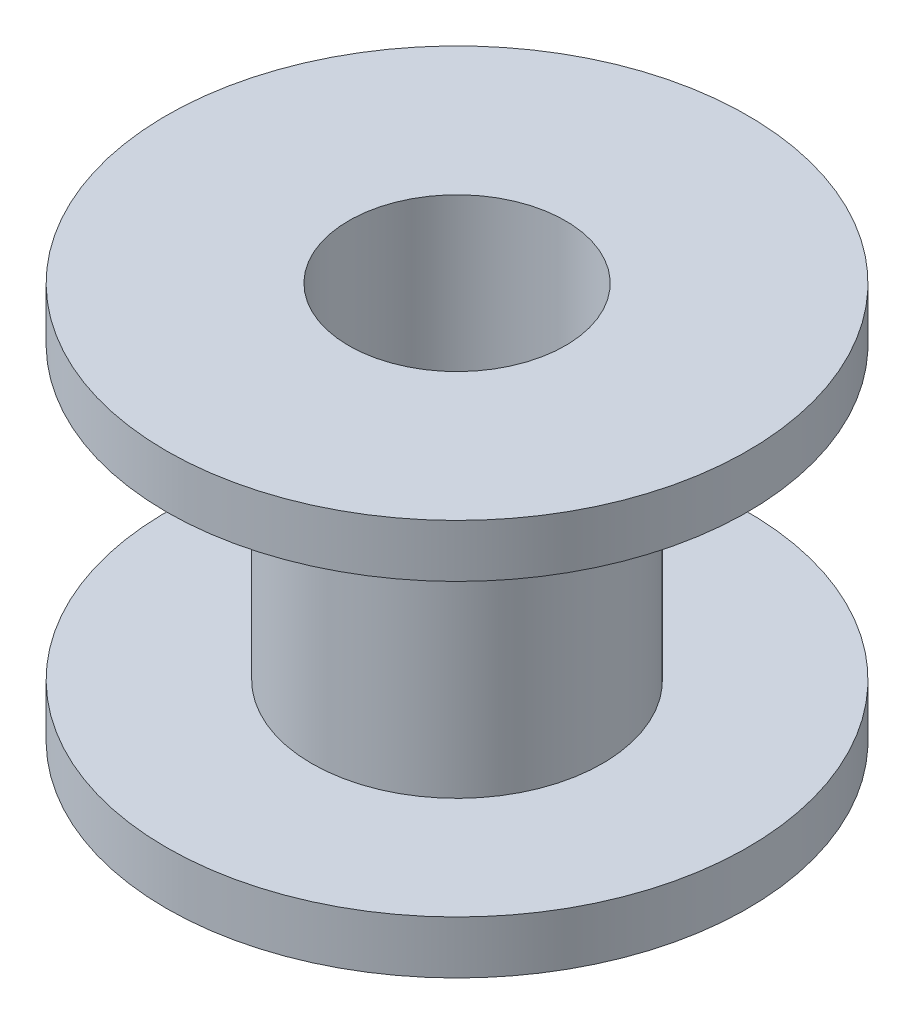
SolidWorks part; units mm, degrees
material "ABS"
ref_plane "Front Plane" through (0, 0, 0) normal (0, 0, 1) x (1, 0, 0)
ref_plane "Top Plane" through (0, 0, 0) normal (0, 1, 0) x (1, 0, 0)
ref_plane "Right Plane" through (0, 0, 0) normal (1, 0, 0) x (0, 0, -1)
sketch "Sketch1" plane through (0, 0, 0) normal (1, 0, 0) x (0, 0, -1)
  line L0 (0, 44.6591) -> (0, -36.1364) construction
  line L1 (-5.5, 5.5) -> (-5.5, -5.5)
  line L2 (-5.5, -5.5) -> (-11, -5.5)
  line L3 (-11, -5.5) -> (-11, -7.5)
  line L4 (-11, -7.5) -> (-4.1, -7.5)
  line L5 (-4.1, -7.5) -> (-4.1, 7.5)
  line L9 (-33.5795, 0) -> (17.0455, 0) construction
  line L10 (-11, 5.5) -> (-11, 7.5)
  line L11 (-11, 7.5) -> (-4.1, 7.5)
  line L12 (-5.5, 5.5) -> (-11, 5.5)
  point P3 (-5.5, 0)
  point P15 (-4.1, 0)
  dimension "D1" = 7.5
  dimension "D2" = 22
  dimension "D3" = 8.2
  dimension "D4" = 2
  dimension "D5" = 11
revolve "Revolve1" add sketch "Sketch1" angle 360 about L0
